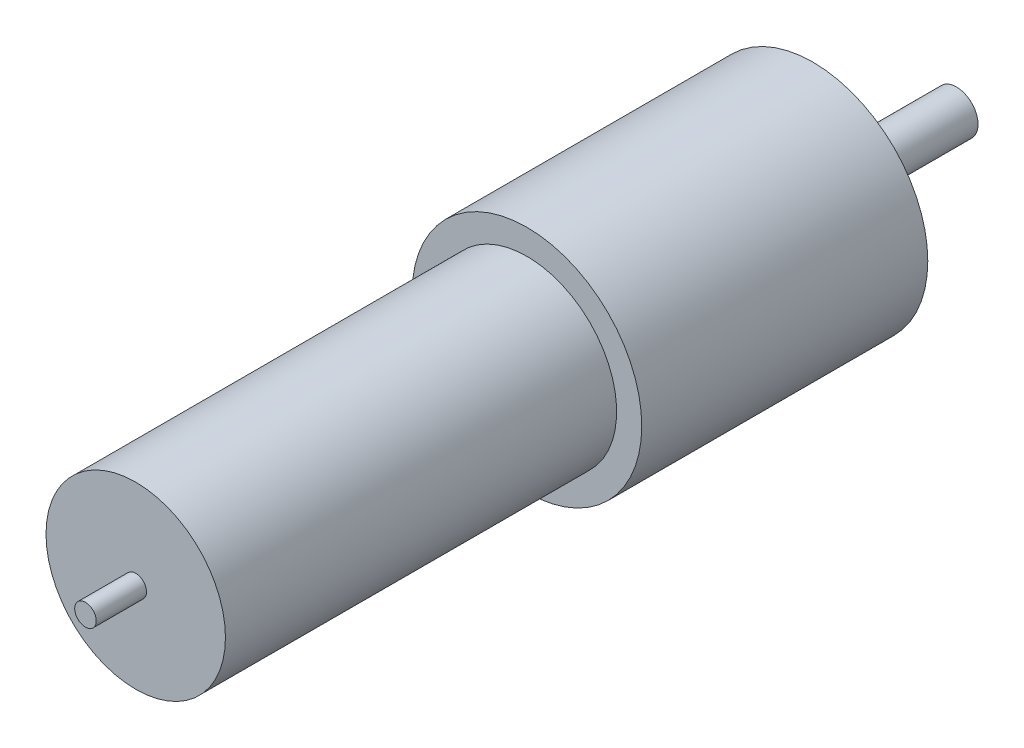
SolidWorks part; units mm, degrees
ref_plane "Plan de face" through (0, 0, 0) normal (0, 0, 1) x (1, 0, 0)
ref_plane "Plan de dessus" through (0, 0, 0) normal (0, 1, 0) x (1, 0, 0)
ref_plane "Plan de droite" through (0, 0, 0) normal (1, 0, 0) x (0, 0, -1)
sketch "Esquisse1" plane through (0, 0, 0) normal (0, 0, 1) x (1, 0, 0)
  circle A0 centre (0, 0) radius 12.5
extrude "Boss.-Extru.1" add sketch "Esquisse1" along normal blind 54.5
sketch "Esquisse2" plane through (0, 0, 54.5) normal (0, 0, 1) x (1, 0, 0)
  circle A0 centre (0, 0) radius 1.5
extrude "Boss.-Extru.2" add sketch "Esquisse2" along normal blind 7
sketch "Esquisse3" plane through (0, 0, 0) normal (0, 0, -1) x (-1, 0, 0)
  circle A0 centre (0, 0) radius 16
extrude "Boss.-Extru.3" add sketch "Esquisse3" along normal blind 39.85
sketch "Esquisse4" plane through (0, 0, -39.85) normal (0, 0, -1) x (-1, 0, 0)
  circle A0 centre (0, 0) radius 3
extrude "Boss.-Extru.8" add sketch "Esquisse4" along normal blind 20
